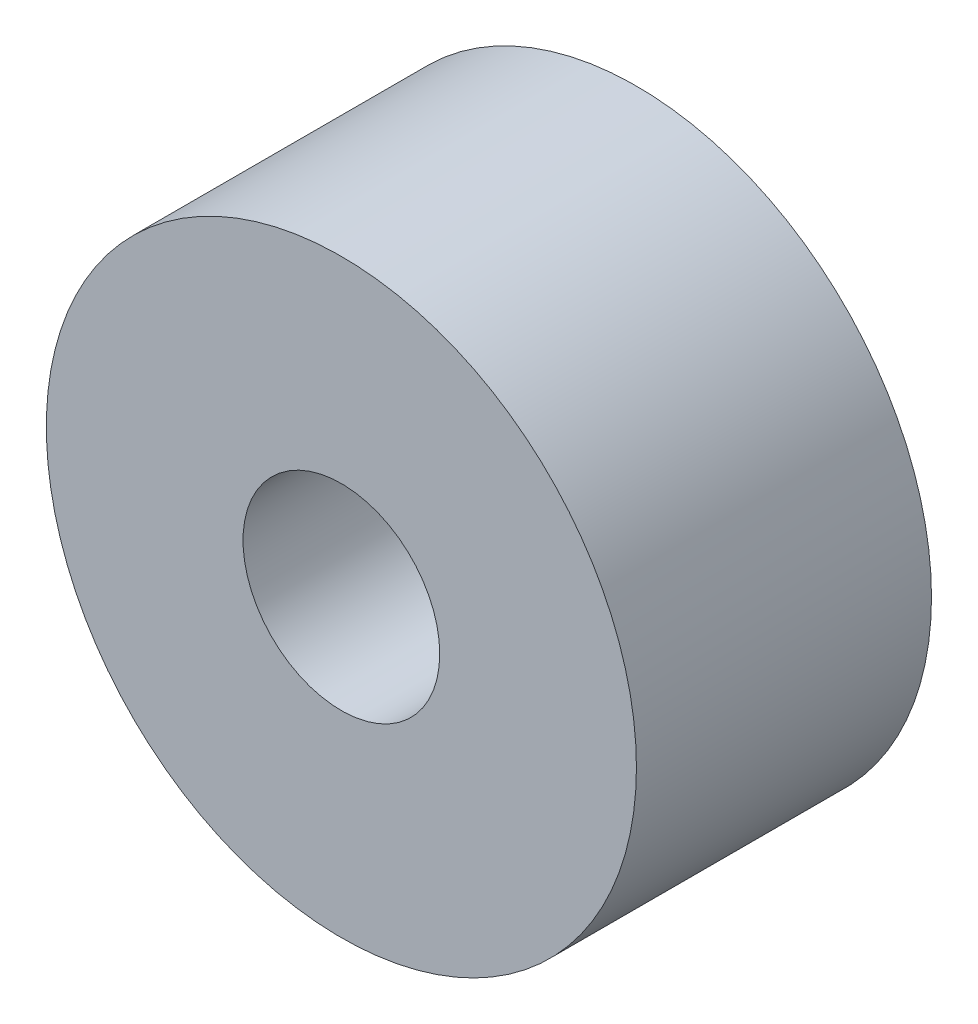
SolidWorks part; units mm, degrees
ref_plane "정면" through (0, 0, 0) normal (0, 0, 1) x (1, 0, 0)
ref_plane "윗면" through (0, 0, 0) normal (0, 1, 0) x (1, 0, 0)
ref_plane "우측면" through (0, 0, 0) normal (1, 0, 0) x (0, 0, -1)
sketch "스케치1" plane through (0, 0, 0) normal (0, 0, 1) x (1, 0, 0)
  circle A0 centre (0, 0) radius 15
  circle A1 centre (0, 0) radius 5
  dimension "D1" = 30
  dimension "D2" = 10
extrude "보스-돌출1" add sketch "스케치1" along normal blind 15
